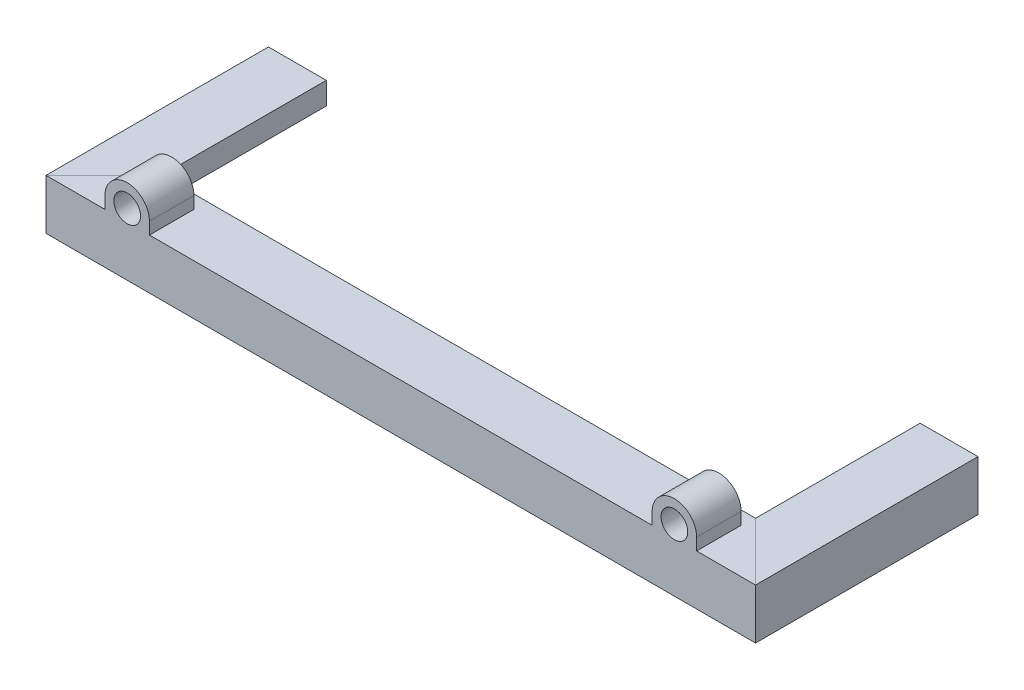
SolidWorks part; units mm, degrees
ref_plane "Alzado" through (0, 0, 0) normal (0, 0, 1) x (1, 0, 0)
ref_plane "Planta" through (0, 0, 0) normal (0, 1, 0) x (1, 0, 0)
ref_plane "Vista lateral" through (0, 0, 0) normal (1, 0, 0) x (0, 0, -1)
sketch "Croquis1" plane through (0, 0, 0) normal (0, 0, 1) x (1, 0, 0)
  line L0 (0, 0) -> (0, 11.3)
  line L1 (0, 11.3) -> (13, 11.3)
  line L2 (13, 11.3) -> (13, 6.3)
  line L3 (13, 6.3) -> (5, 6.3)
  line L4 (5, 6.3) -> (5, 0)
  line L5 (5, 0) -> (0, 0)
  dimension "D1" = 6.3
  dimension "D2" = 5
  dimension "D3" = 8
  dimension "D4" = 5
sketch "Croquis3" plane through (0, 0, 0) normal (0, 1, 0) x (1, 0, 0)
  line L0 (0, 0) -> (0, -50)
  line L1 (0, -50) -> (159.5, -50)
  line L2 (159.5, -50) -> (159.5, 0)
  dimension "D1" = 50
  dimension "D2" = 159.5
  dimension "D3" = 50
sweep "Barrer1" add profiles "Croquis1" path "Croquis3"
ref_plane "Plano1" through (79.75, 0, 0) normal (1, 0, 0) x (0, 0, -1)
ref_plane "Plano2" through (0, 0, 50) normal (0, 0, 1) x (1, 0, 0)
sketch "Croquis4" plane through (0, 0, 50) normal (0, 0, 1) x (1, 0, 0)
  line L0 (0, 11.3) -> (159.5, 11.3) construction
  line L1 (13.25, 11.3) -> (23.25, 11.3)
  line L2 (13.25, 11.3) -> (13.25, 14)
  line L4 (23.25, 11.3) -> (23.25, 14)
  line L5 (0, 11.3) -> (0, 0) construction
  arc A0 (23.25, 14) -> (13.25, 14) centre (18.25, 14) ccw
  dimension "D1" = 2.7
  dimension "D2" = 10
  dimension "D3" = 18.25
extrude "Saliente-Extruir1" add sketch "Croquis4" against normal blind 10
sketch "Croquis5" plane through (0, 0, 50) normal (0, 0, 1) x (1, 0, 0)
  circle A0 centre (18.25, 14) radius 3
  dimension "D1" = 6
extrude "Cortar-Extruir1" cut sketch "Croquis5" against normal through all
mirror "Simetría1" about plane through (79.75, 0, 0) normal (1, 0, 0) of "Cortar-Extruir1", "Saliente-Extruir1"
